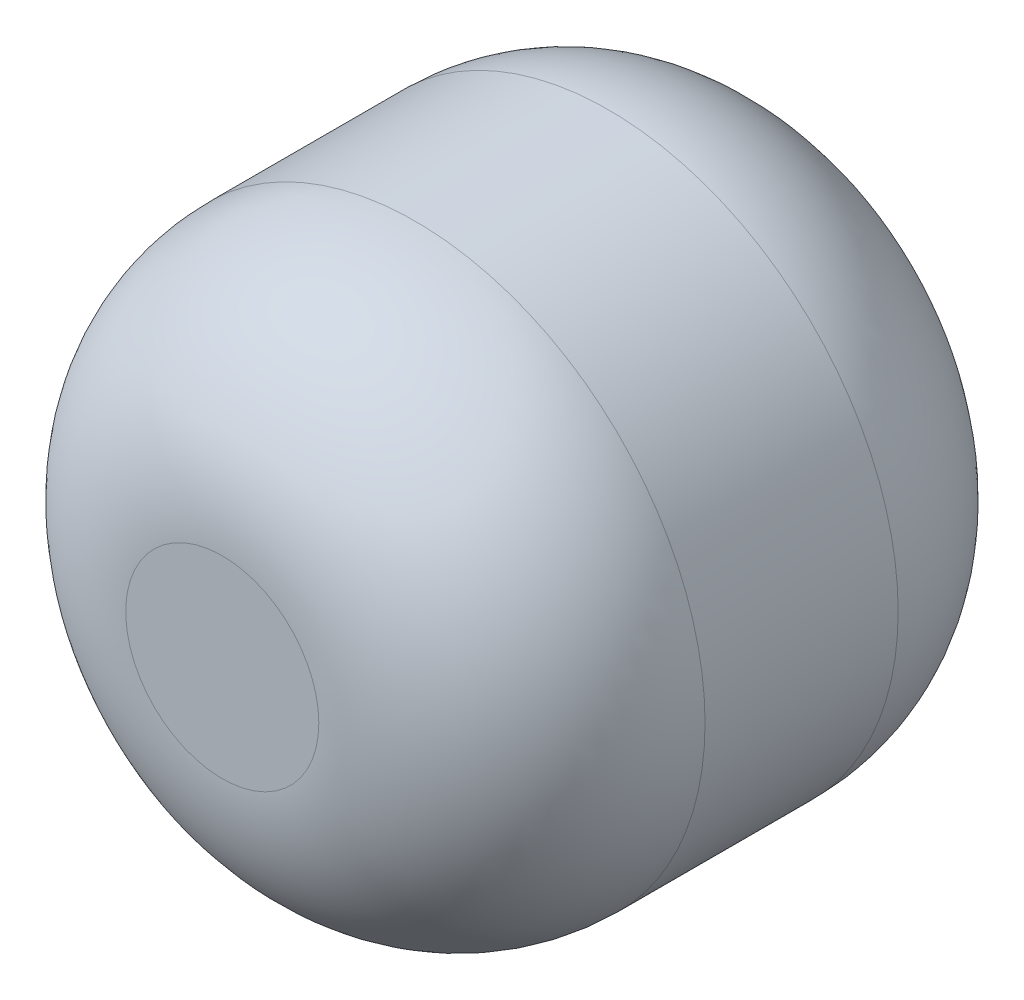
SolidWorks part; units mm, degrees
ref_plane "Plan de face" through (0, 0, 0) normal (0, 0, 1) x (1, 0, 0)
ref_plane "Plan de dessus" through (0, 0, 0) normal (0, 1, 0) x (1, 0, 0)
ref_plane "Plan de droite" through (0, 0, 0) normal (1, 0, 0) x (0, 0, -1)
sketch "Esquisse1" plane through (0, 0, 0) normal (0, 0, 1) x (1, 0, 0)
  circle A0 centre (0, 0) radius 38.1
  dimension "D1" = 76.2
extrude "Boss.-Extru.1" add sketch "Esquisse1" along normal blind 76.2
fillet "Congé1" radius 25.4 2 edges at (38.1, 0, 0) (38.1, 0, 76.2)
